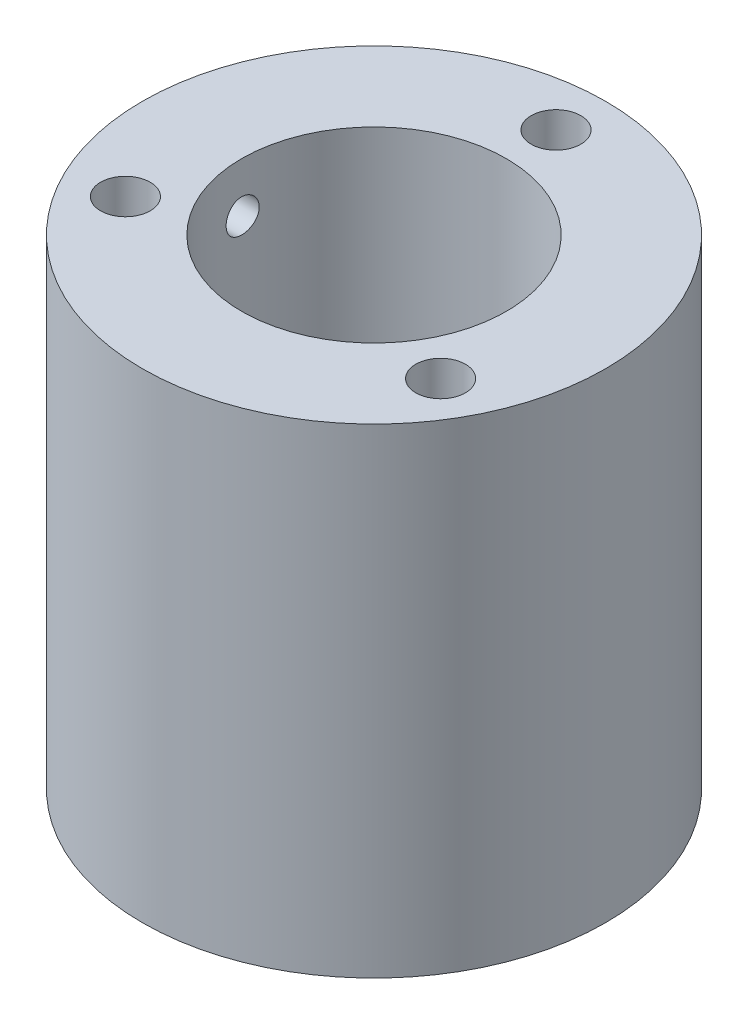
SolidWorks part; units mm, degrees
ref_plane "Plan de face" through (0, 0, 0) normal (0, 0, 1) x (1, 0, 0)
ref_plane "Plan de dessus" through (0, 0, 0) normal (0, 1, 0) x (1, 0, 0)
ref_plane "Plan de droite" through (0, 0, 0) normal (1, 0, 0) x (0, 0, -1)
sketch "Esquisse1" plane through (0, 0, 0) normal (0, 0, 1) x (1, 0, 0)
  line L0 (0, 0) -> (0, 32) construction
  line L1 (8, 0) -> (8, 1.5)
  line L2 (8, 1.5) -> (14, 1.5)
  line L3 (14, 1.5) -> (14, 30.5)
  line L4 (8, 0) -> (3, 0)
  line L7 (3, 0) -> (3, 32)
  line L8 (14, 16) -> (3, 16) construction
  line L9 (3, 16) -> (0, 16) construction
  line L12 (8, 32) -> (3, 32)
  line L13 (8, 30.5) -> (14, 30.5)
  line L14 (8, 32) -> (8, 30.5)
  dimension "D2" = 6
  dimension "D4" = 1.5
  dimension "D5" = 16
  dimension "D6" = 28
  dimension "D7" = 32
revolve "Révolution1" add sketch "Esquisse1" angle 360 about L0
sketch "Esquisse2" plane through (0, 30.5, 0) normal (0, 1, 0) x (1, 0, 0)
  circle A0 centre (0, 0) radius 11 construction
  circle A1 centre (0, 11) radius 1.5
  circle A2 centre (9.5263, -5.5) radius 1.5
  circle A3 centre (-9.5263, -5.5) radius 1.5
  point P11 (0, 0)
  dimension "D1" = 22
  dimension "D2" = 3
  dimension "D3" = 3
extrude "Enlèv. mat.-Extru.1" cut sketch "Esquisse2" against normal blind 10
sketch "Esquisse3" plane through (0, 32, 0) normal (0, 1, 0) x (1, 0, 0)
  circle A0 centre (0, 0) radius 8
extrude "Enlèv. mat.-Extru.2" cut sketch "Esquisse3" against normal blind 25
sketch "Esquisse4" plane through (0, 0, 0) normal (1, 0, 0) x (0, 0, -1)
  line L0 (0, -1.5) -> (0, 31.8415) construction
  line L1 (8, 30.5) -> (-8, 30.5) construction
  circle A0 centre (0, 27.5) radius 1
  dimension "D2" = 2
  dimension "D1" = 3
extrude "Enlèv. mat.-Extru.3" cut sketch "Esquisse4" against normal blind 25
